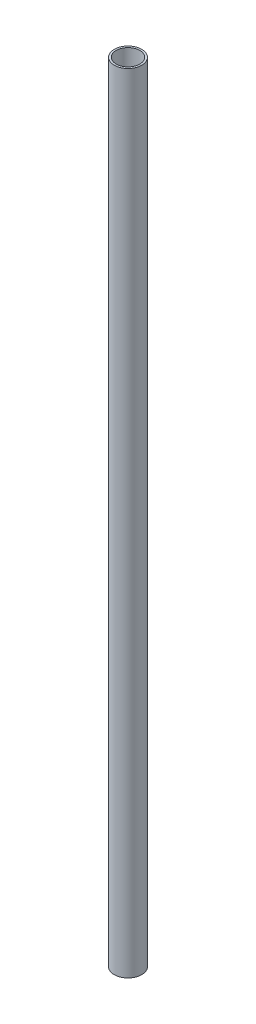
SolidWorks part; units mm, degrees
ref_plane "Front Plane" through (0, 0, 0) normal (0, 0, 1) x (1, 0, 0)
ref_plane "Top Plane" through (0, 0, 0) normal (0, 1, 0) x (1, 0, 0)
ref_plane "Right Plane" through (0, 0, 0) normal (1, 0, 0) x (0, 0, -1)
sketch "Sketch1" plane through (0, 0, 0) normal (0, 1, 0) x (1, 0, 0)
  circle A0 centre (0, 0) radius 9.9
  circle A1 centre (0, 0) radius 11.5
  dimension "D1" = 19.8
  dimension "D2" = 23
extrude "Boss-Extrude1" add sketch "Sketch1" along normal blind 658
